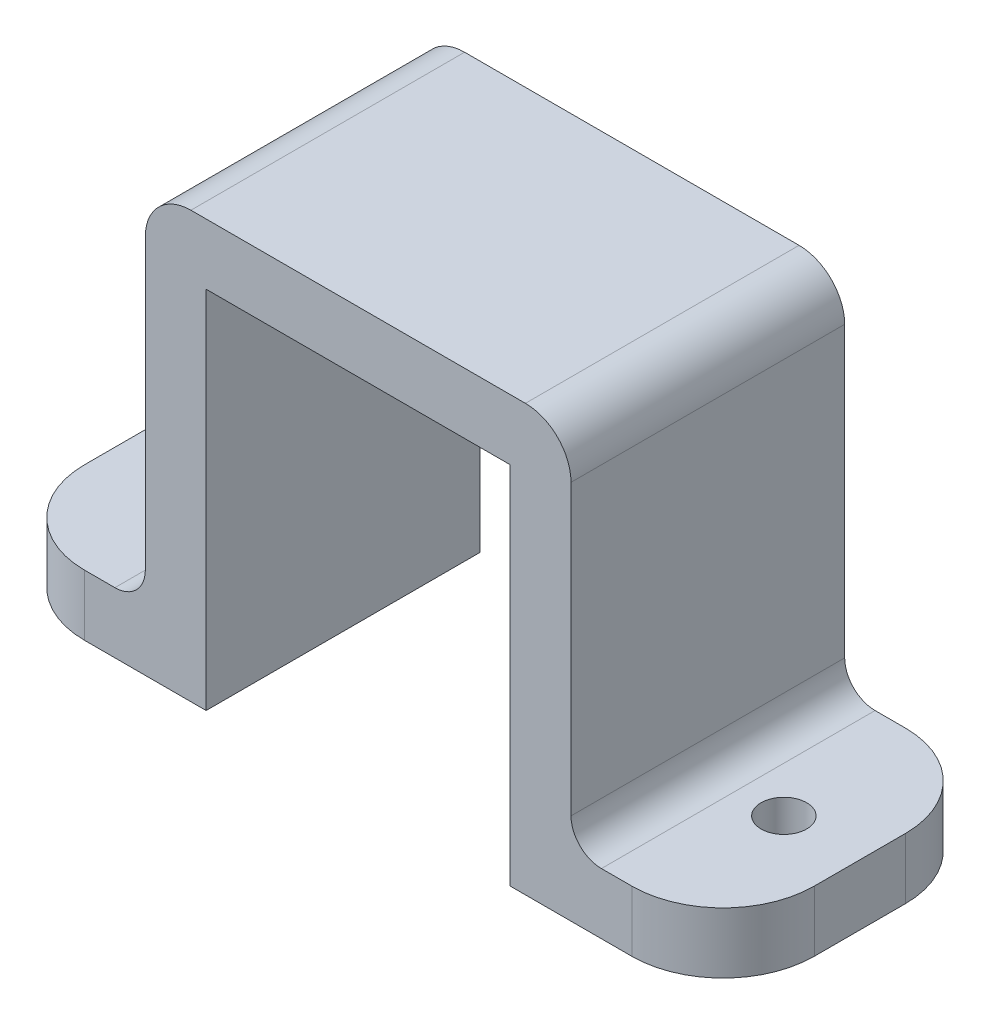
SolidWorks part; units mm, degrees
ref_plane "Alzado" through (0, 0, 0) normal (0, 0, 1) x (1, 0, 0)
ref_plane "Planta" through (0, 0, 0) normal (0, 1, 0) x (1, 0, 0)
ref_plane "Vista lateral" through (0, 0, 0) normal (1, 0, 0) x (0, 0, -1)
sketch "Croquis2" plane through (0, 0, 0) normal (0, 0, 1) x (1, 0, 0)
  line L0 (10, 0) -> (17, 0)
  line L2 (0, 0) -> (0, 12)
  line L3 (0, 12) -> (10, 12)
  line L4 (10, 0) -> (10, 12)
  line L5 (0, 0) -> (-7, 0)
  line L6 (12, 2) -> (17, 2)
  line L7 (12, 2) -> (12, 14)
  line L8 (-2, 14) -> (12, 14)
  line L9 (-2, 2) -> (-2, 14)
  line L10 (-2, 2) -> (-7, 2)
  line L11 (-7, 2) -> (-7, 0)
  line L12 (17, 2) -> (17, 0)
  dimension "D1" = 12
  dimension "D2" = 10
  dimension "D3" = 7
  dimension "D4" = 7
  dimension "D5" = 2
extrude "Saliente-Extruir1" add sketch "Croquis2" along normal blind 9
fillet "Redondeo1" radius 3 4 edges at (-7, 1, 0) (-7, 1, 9) (17, 1, 0) (17, 1, 9)
fillet "Redondeo2" radius 1.5 2 edges at (-2, 14, 4.5) (12, 14, 4.5)
sketch "Croquis3" plane through (0, 2, 0) normal (0, 1, 0) x (1, 0, 0)
  line L0 (12, -9) -> (14, -9)
  line L1 (17, -3) -> (17, -6)
  line L2 (-7, -3) -> (-7, -6)
  circle A0 centre (14.5, -4.5) radius 0.75
  circle A1 centre (-4.5, -4.5) radius 0.75
  dimension "D1" = 1.5
  dimension "D4" = 1.5
  dimension "D2" = 4.5
  dimension "D3" = 2.5
  dimension "D5" = 2.5
extrude "Cortar-Extruir1" cut sketch "Croquis3" against normal blind 9 contours A1 | A0
fillet "Redondeo3" radius 1 2 edges at (-2, 2, 4.5) (12, 2, 4.5)
